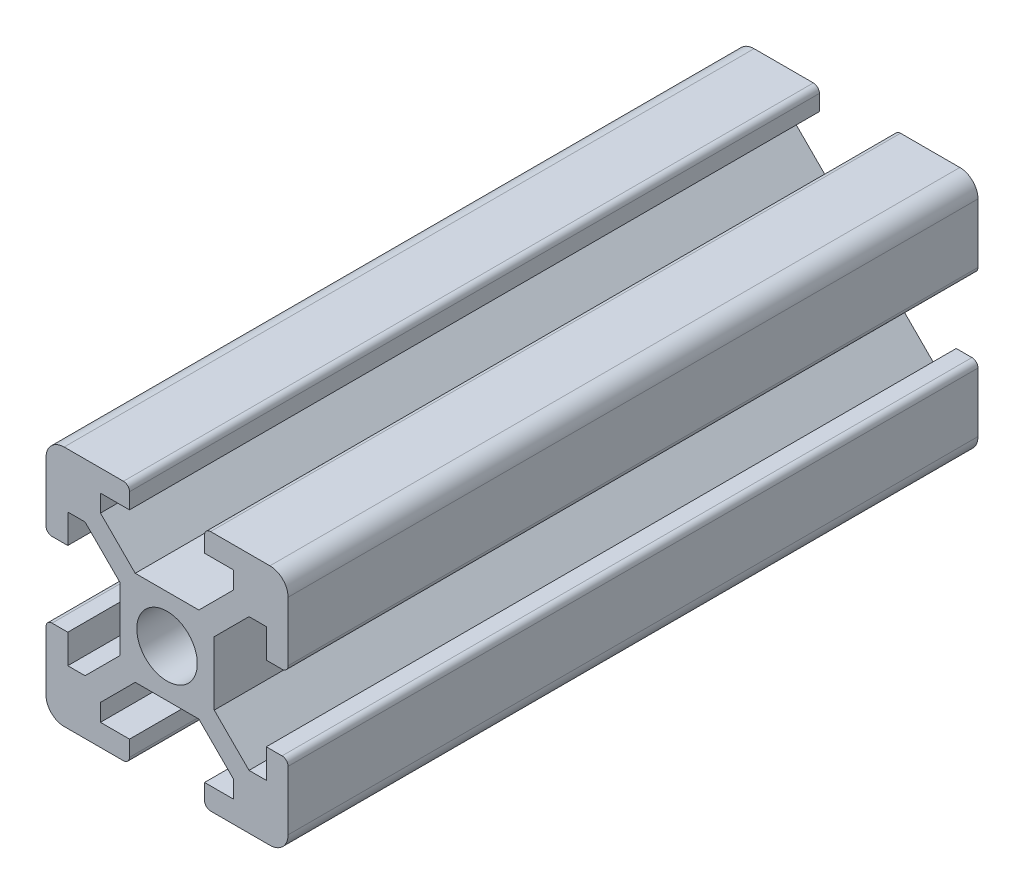
SolidWorks part; units mm, degrees
ref_plane "前视基准面" through (0, 0, 0) normal (0, 0, 1) x (1, 0, 0)
ref_plane "上视基准面" through (0, 0, 0) normal (0, 1, 0) x (1, 0, 0)
ref_plane "右视基准面" through (0, 0, 0) normal (1, 0, 0) x (0, 0, -1)
sketch "草图1" plane through (0, 0, 0) normal (0, 0, 1) x (1, 0, 0)
  line L0 (0, 6.9) -> (0, 0)
  line L1 (20, 20) -> (20, 13.1)
  line L2 (1.8, 15.5) -> (3.2272, 15.5)
  line L3 (4.5, 16.7728) -> (4.5, 18.2)
  line L4 (0, 13.1) -> (0, 20)
  line L5 (6.9, 20) -> (6.9, 18.2)
  line L6 (6.9, 18.2) -> (4.5, 18.2)
  line L7 (13.1, 20) -> (20, 20)
  line L8 (6.9, 20) -> (0, 20)
  line L9 (0, 0) -> (6.9, 0)
  line L10 (13.1, 0) -> (20, 0)
  line L11 (15.5, 18.2) -> (15.5, 16.7728)
  line L12 (16.7728, 15.5) -> (18.2, 15.5)
  line L13 (20, 6.9) -> (20, 0)
  line L14 (1.8, 4.5) -> (3.2272, 4.5)
  line L15 (4.5, 3.2272) -> (4.5, 1.8)
  line L16 (12.6272, 6.1) -> (15.5, 3.2272)
  line L17 (18.2, 4.5) -> (16.7728, 4.5)
  line L18 (15.5, 3.2272) -> (15.5, 1.8)
  line L19 (13.9, 7.3728) -> (16.7728, 4.5)
  line L20 (13.1, 20) -> (13.1, 18.2)
  line L21 (13.1, 18.2) -> (15.5, 18.2)
  line L22 (7.3728, 13.9) -> (12.6272, 13.9)
  line L23 (13.9, 12.6272) -> (13.9, 7.3728)
  line L24 (7.3728, 6.1) -> (12.6272, 6.1)
  line L25 (6.1, 12.6272) -> (6.1, 7.3728)
  line L27 (12.6272, 13.9) -> (15.5, 16.7728)
  line L30 (3.2272, 4.5) -> (6.1, 7.3728)
  line L32 (4.5, 3.2272) -> (7.3728, 6.1)
  line L33 (20, 13.1) -> (18.2, 13.1)
  line L34 (18.2, 13.1) -> (18.2, 15.5)
  line L36 (20, 6.9) -> (18.2, 6.9)
  line L37 (18.2, 6.9) -> (18.2, 4.5)
  line L39 (13.1, 0) -> (13.1, 1.8)
  line L40 (13.1, 1.8) -> (15.5, 1.8)
  line L42 (6.9, 0) -> (6.9, 1.8)
  line L43 (6.9, 1.8) -> (4.5, 1.8)
  line L45 (0, 6.9) -> (1.8, 6.9)
  line L46 (1.8, 6.9) -> (1.8, 4.5)
  line L48 (0, 13.1) -> (1.8, 13.1)
  line L49 (1.8, 13.1) -> (1.8, 15.5)
  line L50 (4.5, 16.7728) -> (7.3728, 13.9)
  line L51 (3.2272, 15.5) -> (6.1, 12.6272)
  line L53 (13.9, 12.6272) -> (16.7728, 15.5)
  line L62 (1.8, 13.1) -> (1.8, 15.5)
  line L63 (0, 13.1) -> (1.8, 13.1)
  line L66 (6.9, 18.2) -> (4.5, 18.2)
  line L67 (6.9, 20) -> (6.9, 18.2)
  line L68 (3.2272, 15.5) -> (1.8, 15.5)
  line L69 (4.5, 18.2) -> (4.5, 16.7728)
  line L75 (4.5, 1.8) -> (4.5, 3.2272)
  line L76 (3.2272, 4.5) -> (1.8, 4.5)
  line L77 (6.9, 0) -> (6.9, 1.8)
  line L78 (6.9, 1.8) -> (4.5, 1.8)
  line L80 (0, 6.9) -> (1.8, 6.9)
  line L81 (1.8, 6.9) -> (1.8, 4.5)
  line L90 (1.8, 6.9) -> (1.8, 4.5)
  line L91 (0, 6.9) -> (1.8, 6.9)
  line L93 (18.2, 6.9) -> (18.2, 4.5)
  line L94 (20, 6.9) -> (18.2, 6.9)
  line L98 (13.1, 1.8) -> (15.5, 1.8)
  line L99 (13.1, 0) -> (13.1, 1.8)
  line L100 (16.7728, 4.5) -> (18.2, 4.5)
  line L101 (15.5, 1.8) -> (15.5, 3.2272)
  line L106 (6.9, 1.8) -> (4.5, 1.8)
  line L107 (6.9, 0) -> (6.9, 1.8)
  line L109 (4.5, 3.2272) -> (4.5, 1.8)
  line L110 (1.8, 4.5) -> (3.2272, 4.5)
  circle A0 centre (10, 10) radius 2.5
extrude "凸台-拉伸1" add sketch "草图1" along normal blind 57 contours L23 L53 L12 L34 L33 L1 L7 L20 L21 L11 L27 L22 L50 L3 L6 L5 L8 L4 L48 L49 L2 L51 L25 L30 L14 L46 L45 L0 L9 L42 L43 L15 L32 L24 L16 L18 L40 L39 L10 L13 L36 L37 L17 L19
fillet "圆角1" radius 1.5 1 edges at (20, 20, 28.5)
fillet "圆角2" radius 1.5 1 edges at (0, 20, 28.5)
fillet "圆角3" radius 1.5 1 edges at (0, 0, 28.5)
fillet "圆角4" radius 1.5 1 edges at (20, 0, 28.5)
fillet "圆角5" radius 0.5 1 edges at (13.1, 20, 28.5)
fillet "圆角6" radius 0.5 1 edges at (6.9, 20, 28.5)
fillet "圆角7" radius 0.5 1 edges at (0, 13.1, 28.5)
fillet "圆角8" radius 0.5 1 edges at (0, 6.9, 28.5)
fillet "圆角9" radius 0.5 1 edges at (6.9, 0, 28.5)
fillet "圆角10" radius 0.5 1 edges at (13.1, 0, 28.5)
fillet "圆角11" radius 0.5 1 edges at (20, 13.1, 28.5)
fillet "圆角12" radius 0.5 1 edges at (20, 6.9, 28.5)
